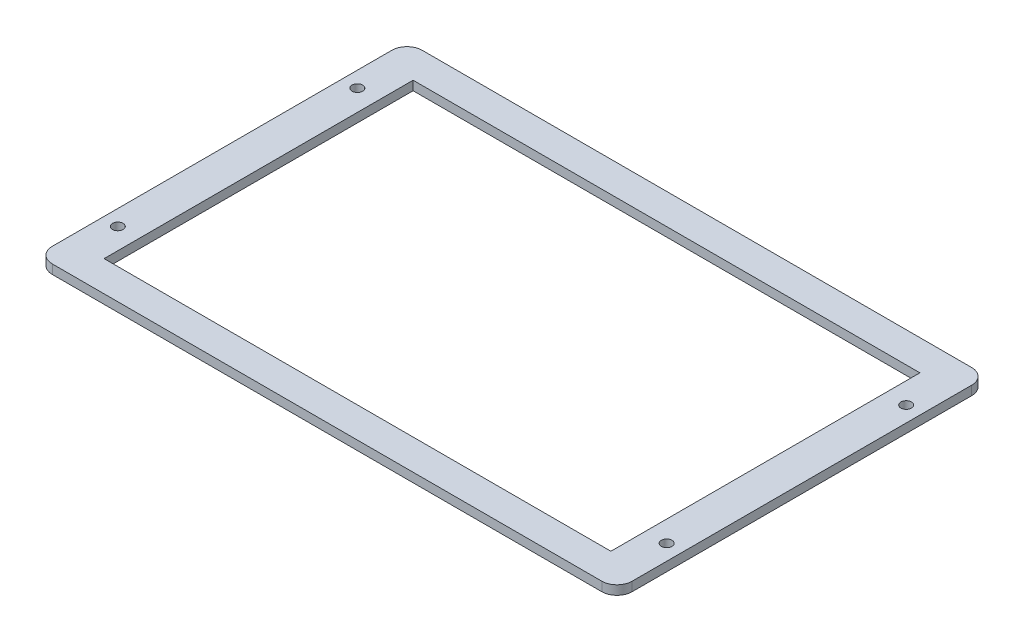
SolidWorks part; units mm, degrees
material "AÇO 1020"
ref_plane "Front Plane" through (0, 0, 0) normal (0, 0, 1) x (1, 0, 0)
ref_plane "Top Plane" through (0, 0, 0) normal (0, 1, 0) x (1, 0, 0)
ref_plane "Right Plane" through (0, 0, 0) normal (1, 0, 0) x (0, 0, -1)
sketch "Sketch1" plane through (0, 0, 0) normal (0, 1, 0) x (1, 0, 0)
  line L1 (95.15, -60.7) -> (-95.15, -60.7)
  line L2 (95.15, -60.7) -> (95.15, 60.7)
  line L3 (95.15, 60.7) -> (-95.15, 60.7)
  line L4 (-95.15, -60.7) -> (-95.15, 60.7)
  line L5 (0, 60.7) -> (0, -60.7) construction
  line L6 (95.15, 0) -> (-95.15, 0) construction
  line L7 (83.15, 50.7) -> (-83.15, 50.7)
  line L8 (83.15, 50.7) -> (83.15, -50.7)
  line L9 (83.15, -50.7) -> (-83.15, -50.7)
  line L10 (-83.15, 50.7) -> (-83.15, -50.7)
  line L11 (0, -50.7) -> (0, 50.7) construction
  line L12 (83.15, 0) -> (-83.15, 0) construction
  point P0 (0, 0)
  point P4 (0, 0)
  dimension "D1" = 12
  dimension "D2" = 10
  dimension "D3" = 166.3
  dimension "D4" = 101.4
extrude "Extrude1" add sketch "Sketch1" along normal blind 3
fillet "Fillet1" radius 5 4 edges at (-95.15, 1.5, 60.7) (-95.15, 1.5, -60.7) (95.15, 1.5, -60.7) (95.15, 1.5, 60.7)
extrude "Cut-Extrude1" cut sketch "Sketch2" against normal blind 3
sketch "Sketch2" plane through (-128.4787, 3, 300.3) normal (0, 1, 0) x (1, 0, 0)
  line L2 (211.6287, 351) -> (45.3287, 351) construction
  line L4 (128.4787, 300.3) -> (128.4787, 351) construction
  circle A0 centre (38.4287, 339.6) radius 1.75
  circle A1 centre (218.5287, 339.6) radius 1.75
  circle A2 centre (218.5287, 261) radius 1.75
  circle A3 centre (38.4287, 261) radius 1.75
  point P12 (0, 0)
  point P13 (0, 0)
  point P14 (36.6787, 261)
  dimension "D3" = 3.5
  dimension "D5" = 39.3
  dimension "D2" = 180.1
  dimension "D4" = 78.6
